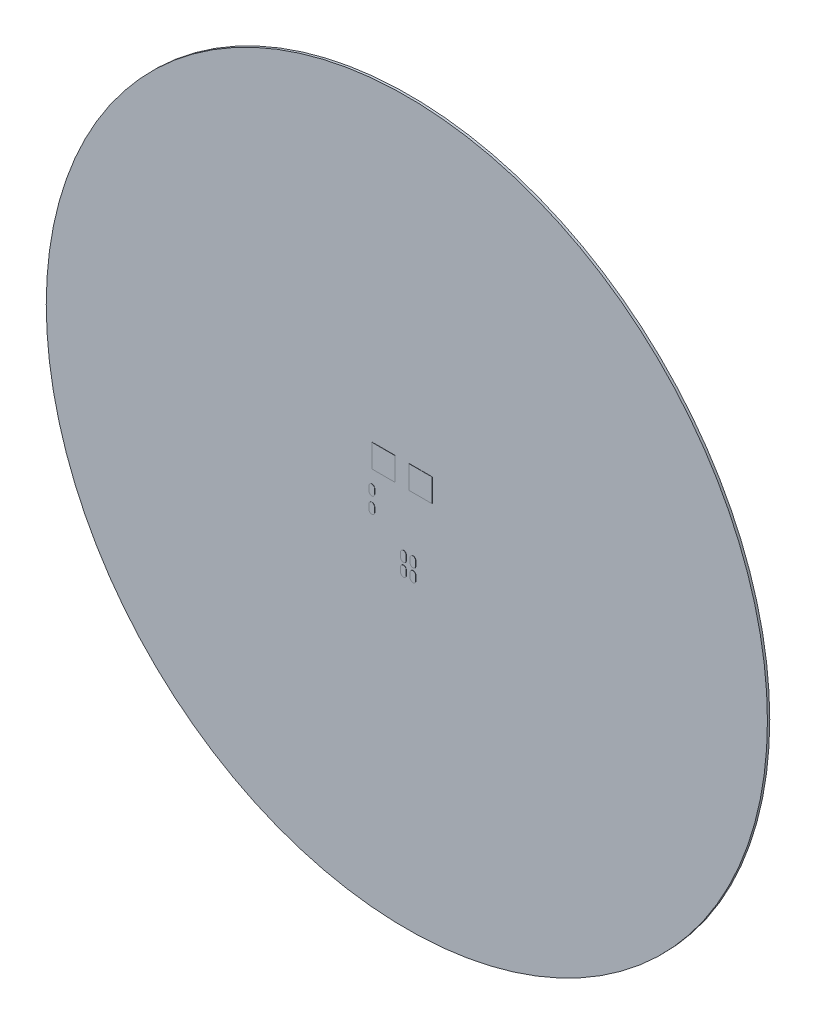
SolidWorks part; units mm, degrees
ref_plane "Front Plane" through (0, 0, 0) normal (0, 0, 1) x (1, 0, 0)
ref_plane "Top Plane" through (0, 0, 0) normal (0, 1, 0) x (1, 0, 0)
ref_plane "Right Plane" through (0, 0, 0) normal (1, 0, 0) x (0, 0, -1)
sketch "Sketch1" plane through (0, 0, 0) normal (0, 0, 1) x (1, 0, 0)
  circle A0 centre (0, 0) radius 155
  dimension "D1" = 310
extrude "Boss-Extrude1" add sketch "Sketch1" along normal blind 1
sketch "Sketch2" plane through (0, 0, 1) normal (0, 0, 1) x (1, 0, 0)
  line L0 (-14.9722, 2.0515) -> (-14.9722, 0) construction
  line L1 (-5.0278, 8.8602) -> (-14.9722, 8.8602)
  line L2 (-5.0278, 8.8602) -> (-5.0278, 18.8047)
  line L3 (-5.0278, 18.8047) -> (-14.9722, 18.8047)
  line L4 (-14.9722, 8.8602) -> (-14.9722, 18.8047)
  line L5 (-5.0278, 8.8602) -> (-14.9722, 18.8047) construction
  line L6 (-5.0278, 18.8047) -> (-14.9722, 8.8602) construction
  line L7 (10.9722, 8.8602) -> (1.0278, 8.8602)
  line L8 (10.9722, 8.8602) -> (10.9722, 18.8047)
  line L9 (10.9722, 18.8047) -> (1.0278, 18.8047)
  line L10 (1.0278, 8.8602) -> (1.0278, 18.8047)
  line L11 (10.9722, 8.8602) -> (1.0278, 18.8047) construction
  line L12 (10.9722, 18.8047) -> (1.0278, 8.8602) construction
  line L13 (-13.7793, 2.0515) -> (-13.7793, 0)
  line L14 (-16.1651, 2.0515) -> (-16.1651, 0)
  line L15 (-14.9722, -6.8029) -> (-14.9722, -4.7514) construction
  line L16 (-16.1651, -6.8029) -> (-16.1651, -4.7514)
  line L17 (-13.7793, -6.8029) -> (-13.7793, -4.7514)
  line L18 (-1.3787, -15.8811) -> (-1.3787, -17.9325) construction
  line L19 (-0.1858, -15.8811) -> (-0.1858, -17.9325)
  line L20 (-2.5716, -15.8811) -> (-2.5716, -17.9325)
  line L21 (2.7072, -15.8811) -> (2.7072, -17.9325) construction
  line L22 (3.9001, -15.8811) -> (3.9001, -17.9325)
  line L23 (1.5143, -15.8811) -> (1.5143, -17.9325)
  line L24 (-1.3787, -21.3936) -> (-1.3787, -23.4451) construction
  line L25 (-0.1858, -21.3936) -> (-0.1858, -23.4451)
  line L26 (-2.5716, -21.3936) -> (-2.5716, -23.4451)
  line L27 (2.7072, -23.4451) -> (2.7072, -21.3936) construction
  line L28 (1.5143, -23.4451) -> (1.5143, -21.3936)
  line L29 (3.9001, -23.4451) -> (3.9001, -21.3936)
  arc A0 (-13.7793, 2.0515) -> (-16.1651, 2.0515) centre (-14.9722, 2.0515) ccw
  arc A1 (-16.1651, 0) -> (-13.7793, 0) centre (-14.9722, 0) ccw
  arc A2 (-16.1651, -6.8029) -> (-13.7793, -6.8029) centre (-14.9722, -6.8029) ccw
  arc A3 (-13.7793, -4.7514) -> (-16.1651, -4.7514) centre (-14.9722, -4.7514) ccw
  arc A4 (-0.1858, -15.8811) -> (-2.5716, -15.8811) centre (-1.3787, -15.8811) ccw
  arc A5 (-2.5716, -17.9325) -> (-0.1858, -17.9325) centre (-1.3787, -17.9325) ccw
  arc A6 (3.9001, -15.8811) -> (1.5143, -15.8811) centre (2.7072, -15.8811) ccw
  arc A7 (1.5143, -17.9325) -> (3.9001, -17.9325) centre (2.7072, -17.9325) ccw
  arc A8 (-0.1858, -21.3936) -> (-2.5716, -21.3936) centre (-1.3787, -21.3936) ccw
  arc A9 (-2.5716, -23.4451) -> (-0.1858, -23.4451) centre (-1.3787, -23.4451) ccw
  arc A10 (1.5143, -23.4451) -> (3.9001, -23.4451) centre (2.7072, -23.4451) ccw
  arc A11 (3.9001, -21.3936) -> (1.5143, -21.3936) centre (2.7072, -21.3936) ccw
  point P0 (-10, 13.8324)
  point P5 (6, 13.8324)
  point P10 (-14.9722, 1.0257)
  point P18 (-14.9722, -5.7771)
  point P25 (-1.3787, -16.9068)
  point P32 (2.7072, -16.9068)
  point P39 (-1.3787, -22.4194)
  point P46 (2.7072, -22.4194)
  point P53 (0, 0)
  point P54 (0, 0)
  point P55 (-1.4051, -20.2259)
  point P56 (-1.3787, -16.4093)
  point P57 (2.7072, -16.9068)
  dimension "D1" = 10
  dimension "D2" = 6
extrude "Boss-Extrude2" add sketch "Sketch2" along normal blind 0.1
